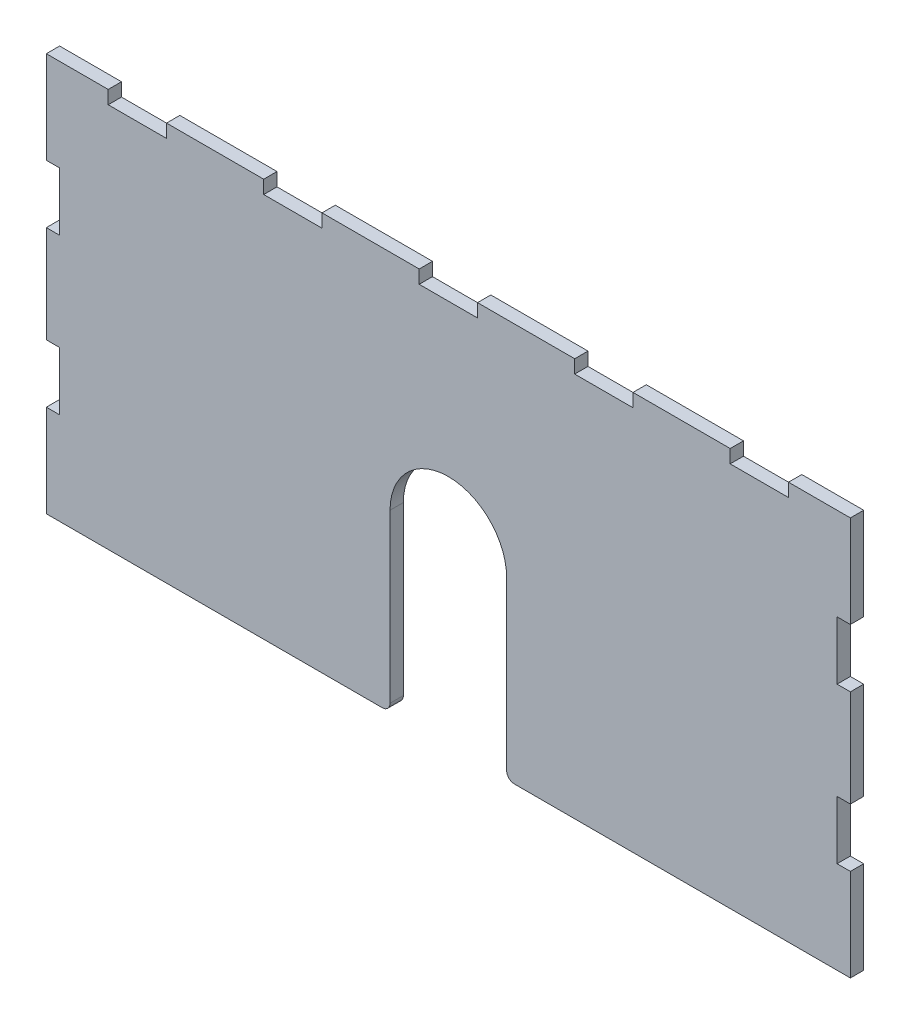
SolidWorks part; units mm, degrees
ref_plane "Front Plane" through (0, 0, 0) normal (0, 0, 1) x (1, 0, 0)
ref_plane "Top Plane" through (0, 0, 0) normal (0, 1, 0) x (1, 0, 0)
ref_plane "Right Plane" through (0, 0, 0) normal (1, 0, 0) x (0, 0, -1)
sketch "Sketch1" plane through (0, 0, 0) normal (0, 0, 1) x (1, 0, 0)
  line L1 (-131.3434, -65.0875) -> (131.3434, -65.0875)
  line L2 (-131.3434, -65.0875) -> (-131.3434, 65.0875)
  line L3 (-131.3434, 65.0875) -> (131.3434, 65.0875)
  line L4 (131.3434, -65.0875) -> (131.3434, 65.0875)
  line L5 (-131.3434, -65.0875) -> (131.3434, 65.0875) construction
  line L6 (-131.3434, 65.0875) -> (131.3434, -65.0875) construction
  point P0 (0, 0)
  dimension "D1" = 262.6868
  dimension "D2" = 130.175
extrude "Boss-Extrude1" add sketch "Sketch1" along normal blind 4.3434
sketch "Sketch2" plane through (0, 0, 4.3434) normal (0, 0, 1) x (1, 0, 0)
  line L2 (-60.325, 60.7441) -> (-41.275, 60.7441)
  line L3 (-60.325, 60.7441) -> (-60.325, 69.4309)
  line L4 (-60.325, 69.4309) -> (-41.275, 69.4309)
  line L5 (-41.275, 60.7441) -> (-41.275, 69.4309)
  line L6 (-60.325, 60.7441) -> (-41.275, 69.4309) construction
  line L7 (131.3434, 65.0875) -> (-131.3434, 65.0875) construction
  line L8 (-9.525, 60.7441) -> (9.525, 60.7441)
  line L9 (-9.525, 60.7441) -> (-9.525, 69.4309)
  line L10 (-9.525, 69.4309) -> (9.525, 69.4309)
  line L11 (9.525, 60.7441) -> (9.525, 69.4309)
  line L12 (-9.525, 60.7441) -> (9.525, 69.4309) construction
  line L13 (-9.525, 69.4309) -> (9.525, 60.7441) construction
  line L14 (41.275, 69.4309) -> (60.325, 69.4309)
  line L15 (60.325, 60.7441) -> (60.325, 69.4309)
  line L16 (41.275, 60.7441) -> (60.325, 60.7441)
  line L17 (41.275, 60.7441) -> (41.275, 69.4309)
  line L18 (92.075, 69.4309) -> (111.125, 69.4309)
  line L19 (111.125, 60.7441) -> (111.125, 69.4309)
  line L20 (92.075, 60.7441) -> (111.125, 60.7441)
  line L21 (92.075, 60.7441) -> (92.075, 69.4309)
  line L22 (-60.325, 69.4309) -> (-41.275, 60.7441) construction
  line L23 (-111.125, 60.7441) -> (-92.075, 60.7441)
  line L24 (-111.125, 60.7441) -> (-111.125, 69.4309)
  line L25 (-111.125, 69.4309) -> (-92.075, 69.4309)
  line L26 (-92.075, 60.7441) -> (-92.075, 69.4309)
  line L27 (-111.125, 60.7441) -> (-92.075, 69.4309) construction
  line L28 (-111.125, 69.4309) -> (-92.075, 60.7441) construction
  line L29 (-131.3434, 65.0875) -> (-131.3434, -65.0875) construction
  point P1 (-50.8, 65.0875)
  point P7 (0, 65.0875)
  point P15 (-101.6, 65.0875)
  point P32 (97.2566, 69.4309)
  dimension "D1" = 3
  dimension "D2" = 8.6868
  dimension "D3" = 19.05
  dimension "D4" = 121.8184
  dimension "D7" = 3
extrude "Cut-Extrude1" cut sketch "Sketch2" against normal through all
sketch "Sketch3" plane through (0, 0, 4.3434) normal (0, 0, 1) x (1, 0, 0)
  line L0 (-131.3434, 65.0875) -> (-131.3434, -65.0875) construction
  line L1 (-135.6868, -34.925) -> (-127, -34.925)
  line L2 (-135.6868, -34.925) -> (-135.6868, -15.875)
  line L3 (-135.6868, -15.875) -> (-127, -15.875)
  line L4 (-127, -34.925) -> (-127, -15.875)
  line L5 (-135.6868, -34.925) -> (-127, -15.875) construction
  line L6 (-135.6868, -15.875) -> (-127, -34.925) construction
  line L7 (-131.3434, -65.0875) -> (131.3434, -65.0875) construction
  line L9 (-135.6868, 34.925) -> (-127, 34.925)
  line L10 (-135.6868, 15.875) -> (-127, 15.875)
  line L11 (-127, 15.875) -> (-127, 34.925)
  line L12 (-135.6868, 15.875) -> (-135.6868, 34.925)
  point P0 (-131.3434, -25.4)
  dimension "D1" = 8.6868
  dimension "D2" = 39.6875
  dimension "D3" = 19.05
  dimension "D4" = 2
sketch "Sketch4" plane through (0, 0, 4.3434) normal (0, 0, 1) x (1, 0, 0)
  line L0 (0, -65.0875) -> (0, -7.9375) construction
  line L1 (-131.3434, -65.0875) -> (131.3434, -65.0875) construction
  line L2 (-19.05, -65.0875) -> (-19.05, -7.9375)
  line L3 (19.05, -65.0875) -> (19.05, -7.9375)
  arc A0 (-19.05, -65.0875) -> (19.05, -65.0875) centre (0, -65.0875) ccw
  arc A1 (19.05, -7.9375) -> (-19.05, -7.9375) centre (0, -7.9375) ccw
  point P5 (0, -36.5125)
  dimension "D1" = 38.1
  dimension "D2" = 57.15
extrude "Cut-Extrude2" cut sketch "Sketch4" against normal through all
extrude "Cut-Extrude3" cut sketch "Sketch3" against normal through all
mirror "Mirror1" about plane through (0, 0, 0) normal (1, 0, 0) of "Cut-Extrude3"
fillet "Fillet1" radius 2.54 2 edges at (19.05, -65.0875, 2.1717) (-19.05, -65.0875, 2.1717)
